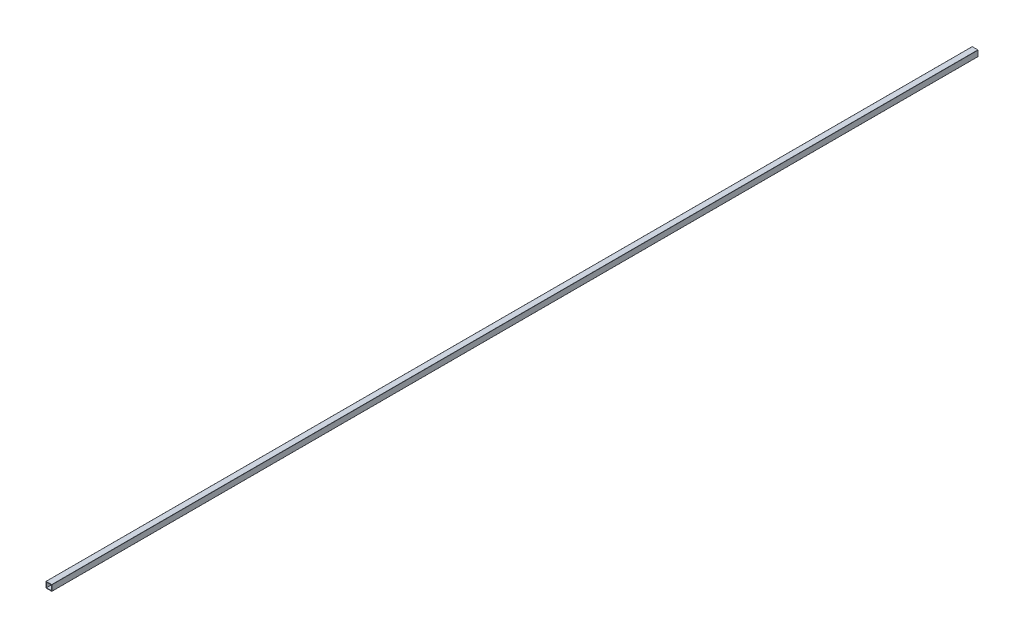
SolidWorks part; units mm, degrees
material "AISI 1035 Acero (SS)"
ref_plane "Alzado" through (0, 0, 0) normal (0, 0, 1) x (1, 0, 0)
ref_plane "Planta" through (0, 0, 0) normal (0, 1, 0) x (1, 0, 0)
ref_plane "Vista lateral" through (0, 0, 0) normal (1, 0, 0) x (0, 0, -1)
sketch "Croquis1" plane through (0, 0, 0) normal (0, 0, 1) x (1, 0, 0)
  line L0 (-16.01, -16.01) -> (-16.01, 16.01)
  line L1 (-18.05, -19.05) -> (18.05, -19.05)
  line L2 (-19.05, -18.05) -> (-19.05, 18.05)
  line L3 (-18.05, 19.05) -> (18.05, 19.05)
  line L4 (19.05, -18.05) -> (19.05, 18.05)
  line L5 (-19.05, -19.05) -> (19.05, 19.05) construction
  line L6 (-19.05, 19.05) -> (19.05, -19.05) construction
  line L7 (-16.01, 16.01) -> (16.01, 16.01)
  line L8 (16.01, -16.01) -> (16.01, 16.01)
  line L9 (-16.01, -16.01) -> (16.01, -16.01)
  line L10 (-19.05, 19.05) -> (19.05, 19.05) construction
  line L11 (19.05, -19.05) -> (19.05, 19.05) construction
  line L12 (-19.05, -19.05) -> (19.05, -19.05) construction
  line L13 (-19.05, -19.05) -> (-19.05, 19.05) construction
  arc A0 (18.05, 19.05) -> (19.05, 18.05) centre (18.05, 18.05) cw
  arc A1 (18.05, -19.05) -> (19.05, -18.05) centre (18.05, -18.05) ccw
  arc A2 (-18.05, -19.05) -> (-19.05, -18.05) centre (-18.05, -18.05) cw
  arc A3 (-19.05, 18.05) -> (-18.05, 19.05) centre (-18.05, 18.05) cw
  point P0 (0, 0)
  dimension "D2" = 1
  dimension "D1" = 38.1
  dimension "D3" = 3.04
extrude "Saliente-Extruir1" add sketch "Croquis1" along normal blind 6000
